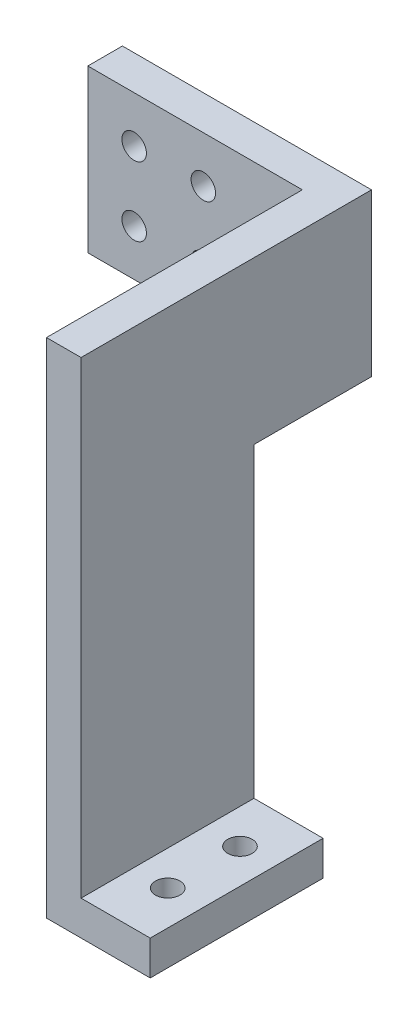
SolidWorks part; units mm, degrees
material "6061 Alloy"
ref_plane "Front" through (0, 0, 0) normal (0, 0, 1) x (1, 0, 0)
ref_plane "Top" through (0, 0, 0) normal (0, 1, 0) x (1, 0, 0)
ref_plane "Right" through (0, 0, 0) normal (1, 0, 0) x (0, 0, -1)
sketch "Sketch1" plane through (0, 0, 0) normal (0, 1, 0) x (1, 0, 0)
  line L0 (0, -15.875) -> (0, 15.875) construction
  line L1 (-9.525, -15.875) -> (9.525, -15.875)
  line L2 (-9.525, -15.875) -> (-9.525, 15.875)
  line L3 (-9.525, 15.875) -> (9.525, 15.875)
  line L4 (9.525, -15.875) -> (9.525, 15.875)
  dimension "D1" = 31.75
  dimension "D2" = 19.05
extrude "Extrude1" add sketch "Sketch1" along normal blind 6.35
sketch "Sketch3" plane through (0, 6.35, 0) normal (0, 1, 0) x (1, 0, 0)
  line L0 (-9.525, -15.875) -> (9.525, -15.875) construction
  line L1 (-9.525, 15.875) -> (-3.175, 15.875)
  line L2 (-9.525, 15.875) -> (-9.525, -15.875)
  line L3 (-9.525, -15.875) -> (-3.175, -15.875)
  line L4 (-3.175, 15.875) -> (-3.175, -15.875)
  dimension "D1" = 6.35
extrude "Extrude2" add sketch "Sketch3" along normal blind 85.9886
sketch "Sketch4" plane through (0, 0, -15.875) normal (0, 0, -1) x (-1, 0, 0)
  line L0 (9.525, 92.3386) -> (9.525, 0) construction
  line L1 (3.175, 92.3386) -> (9.525, 92.3386)
  line L2 (3.175, 92.3386) -> (3.175, 62.6206)
  line L3 (3.175, 62.6206) -> (9.525, 62.6206)
  line L4 (9.525, 92.3386) -> (9.525, 62.6206)
  dimension "D1" = 29.718
extrude "Extrude3" add sketch "Sketch4" along normal blind 21.59
sketch "Sketch5" plane through (-9.525, 0, 0) normal (-1, 0, 0) x (0, 0, 1)
  line L0 (-37.465, 62.6206) -> (-15.875, 62.6206) construction
  line L1 (-37.465, 92.3386) -> (-31.115, 92.3386)
  line L2 (-37.465, 92.3386) -> (-37.465, 62.6206)
  line L3 (-37.465, 62.6206) -> (-31.115, 62.6206)
  line L4 (-31.115, 92.3386) -> (-31.115, 62.6206)
  dimension "D1" = 6.35
extrude "Extrude4" add sketch "Sketch5" along normal blind 39.399
hole_wizard "M4 Clearance Hole1" positions "Sketch7" profile "Sketch6" hole size "M4" standard "Ansi Metric" end condition through all
sketch "Sketch7" plane through (30.89, -14.859, -37.465) normal (0, 0, -1) x (-1, 0, 0)
  circle A0 centre (71.305, 98.6886) radius 2.0828 construction
  circle A1 centre (58.605, 98.6886) radius 2.0828 construction
  circle A2 centre (58.605, 85.9886) radius 2.0828 construction
  circle A3 centre (71.305, 85.9886) radius 2.0828 construction
  point P0 (71.305, 85.9886)
  point P1 (58.605, 85.9886)
  point P3 (58.605, 98.6886)
  point P5 (71.305, 98.6886)
sketch "Sketch6" plane through (-40.415, 71.1296, -37.465) normal (1, 0, 0) x (0, 1, 0)
  line L0 (0, 0) -> (0, 53.34)
  line L1 (0, 53.34) -> (2.25, 53.34)
  line L2 (2.25, 53.34) -> (2.25, 0)
  line L5 (2.25, 0) -> (0, 0)
  line L11 (0, -6.35) -> (0, 107.95) construction
  dimension "Thru Hole Dia." = 4.5
  dimension "Thru Hole Depth" = 53.34
hole_wizard "M4 Clearance Hole2" positions "Sketch10" profile "Sketch9" hole size "M4" standard "Ansi Metric" end condition through all
sketch "Sketch10" plane through (0, 6.35, 0) normal (0, 1, 0) x (-1, 0, 0)
  line L0 (-3.175, 15.875) -> (-3.175, -15.875) construction
  line L1 (3.175, 15.875) -> (-9.525, 15.875) construction
  line L2 (-9.525, -15.875) -> (3.175, -15.875) construction
  line L4 (-3.175, 6.3131) -> (-3.175, -6.9566) construction
  line L6 (-3.175, 0) -> (-6.1047, 0) construction
  line L8 (-3.175, 0) -> (-5.6097, 0) construction
  point P0 (-3.175, 6.3131)
  point P1 (-3.175, -6.9566)
sketch "Sketch9" plane through (3.175, 6.35, 6.3131) normal (1, 0, 0) x (0, 0, 1)
  line L0 (0, 0) -> (0, 6.35)
  line L1 (0, 6.35) -> (2.25, 6.35)
  line L2 (2.25, 6.35) -> (2.25, 0)
  line L5 (2.25, 0) -> (0, 0)
  line L11 (0, -6.35) -> (0, 107.95) construction
  dimension "Thru Hole Dia." = 4.5
  dimension "Thru Hole Depth" = 6.35
